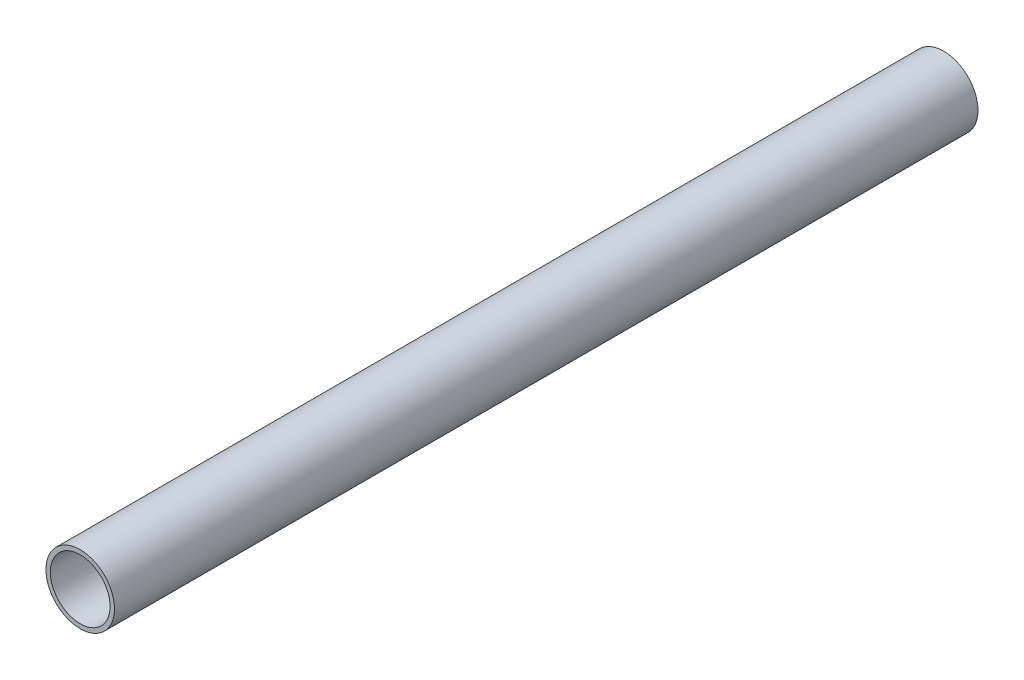
SolidWorks part; units mm, degrees
material "Copper"
ref_plane "Front" through (0, 0, 0) normal (0, 0, 1) x (1, 0, 0)
ref_plane "Top" through (0, 0, 0) normal (0, 1, 0) x (1, 0, 0)
ref_plane "Right" through (0, 0, 0) normal (1, 0, 0) x (0, 0, -1)
sketch "Sketch1" plane through (0, 0, 0) normal (0, 0, 1) x (1, 0, 0)
  circle A0 centre (0, 0) radius 7.9375
  circle A1 centre (0, 0) radius 6.9215
  dimension "D1" = 15.875
  dimension "D2" = 13.843
extrude "Boss-Extrude1" add sketch "Sketch1" along normal mid plane 200
